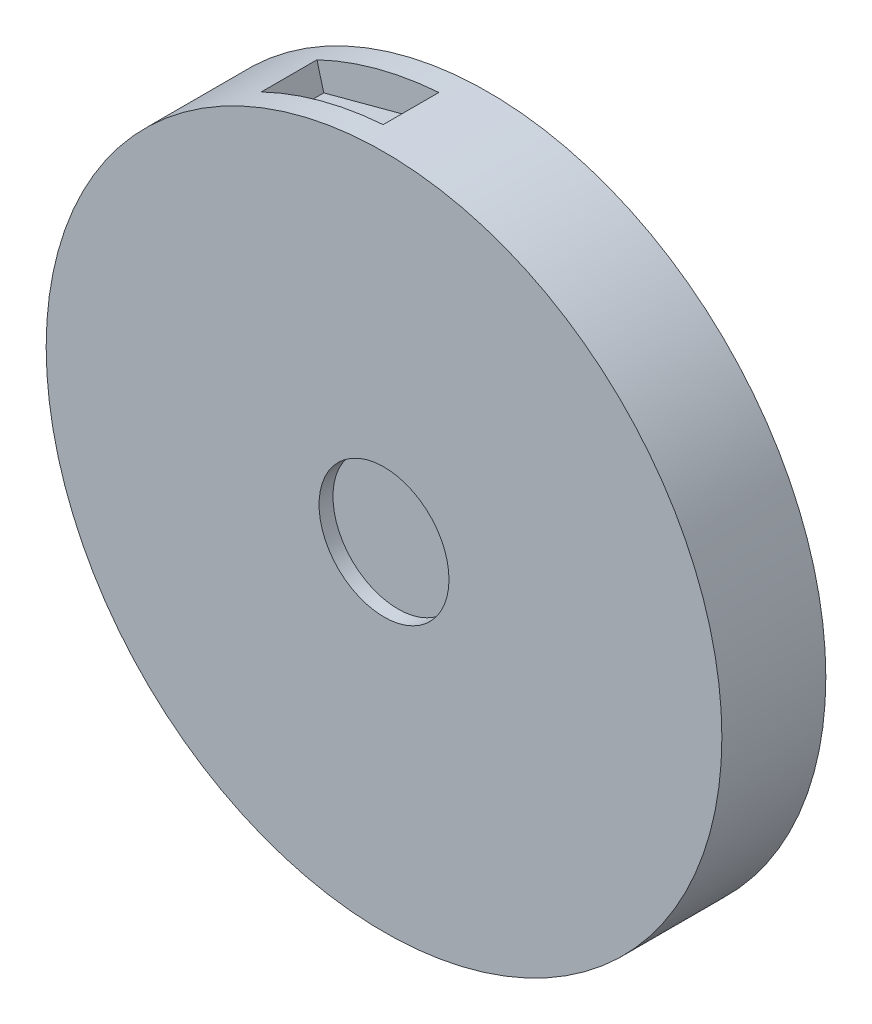
SolidWorks part; units mm, degrees
material "7075-T6, Plate (SS)"
ref_plane "Front" through (0, 0, 0) normal (0, 0, 1) x (1, 0, 0)
ref_plane "Top" through (0, 0, 0) normal (0, 1, 0) x (1, 0, 0)
ref_plane "Right" through (0, 0, 0) normal (1, 0, 0) x (0, 0, -1)
sketch "Sketch1" plane through (0, 0, 0) normal (0, 0, 1) x (1, 0, 0)
  circle A1 centre (0, 0) radius 18.2
  dimension "D1" = 36.4
extrude "Boss-Extrude1" add sketch "Sketch1" along normal blind 5.6 separate body
sketch "Sketch2" plane through (0, 0, 0) normal (0, 0, -1) x (-1, 0, 0)
  line L0 (-11.1314, -13.5034) -> (11.1314, 13.5034) construction
  line L1 (0, 0) -> (13.5086, 0) construction
  line L2 (0, 0) -> (15.6152, -12.8722) construction
  arc A2 (12.9625, -11.7568) -> (14.0142, -10.4811) centre (0, 0) ccw
  arc A3 (-12.4066, -12.1331) -> (-9.5429, -14.4937) centre (-11.4494, -13.8892) cw
  arc A4 (-9.5429, -14.4937) -> (-9.4604, -14.7225) centre (-9.3523, -14.5542) ccw
  arc A5 (-12.4066, -12.1331) -> (-12.6468, -12.0958) centre (-12.5023, -11.9575) cw
  arc A6 (12.4066, 12.1331) -> (12.6468, 12.0958) centre (12.5023, 11.9575) cw
  arc A7 (9.5429, 14.4937) -> (12.4066, 12.1331) centre (11.4494, 13.8892) ccw
  arc A8 (9.5429, 14.4937) -> (9.4604, 14.7225) centre (9.3523, 14.5542) ccw
  arc A10 (13.0025, -11.5546) -> (13.8233, -10.5589) centre (13.708, -11.3) cw
  arc A11 (13.8233, -10.5589) -> (14.0142, -10.4811) centre (13.854, -10.3613) ccw
  arc A12 (13.0025, -11.5546) -> (12.9625, -11.7568) centre (12.8144, -11.6224) cw
  arc A13 (12.6468, 12.0958) -> (9.4604, 14.7225) centre (0, 0) ccw
  arc A14 (-12.6468, -12.0958) -> (-9.4604, -14.7225) centre (0, 0) ccw
  dimension "D3" = 2
  dimension "D4" = 0.2
  dimension "D7" = 0.75
  dimension "D1" = 35
  dimension "D2" = 50.5
  dimension "D5" = 4.1295
  dimension "D6" = 1.6533
extrude "Cut-Extrude1" cut sketch "Sketch2" against normal blind 4
sketch "Sketch3" plane through (0, 0, 5.6) normal (0, 0, 1) x (1, 0, 0)
  circle A0 centre (0, 0) radius 3.5
  dimension "D1" = 7
extrude "Cut-Extrude2" cut sketch "Sketch3" against normal blind 0.75
sketch "Sketch4" plane through (0, 0, 0) normal (0, 1, 0) x (1, 0, 0)
  line L0 (0, 0) -> (0, 23.9004) construction
ref_plane "Plane1" through (0, 0, 0) normal (-0.2588, 0.9659, 0) x (0, 0, -1)
sketch "Sketch5" plane through (0, 0, 0) normal (-0.2588, 0.9659, 0) x (0, 0, -1)
  line L0 (0, 0) -> (23.9004, 0) construction
  line L1 (-4.3, 3.4) -> (-1.3, 3.4)
  line L2 (-4.3, 3.4) -> (-4.3, -3.4)
  line L3 (-4.3, -3.4) -> (-1.3, -3.4)
  line L4 (-1.3, 3.4) -> (-1.3, -3.4)
  line L5 (0, -18.2) -> (0, 18.2) construction
  point P4 (-1.3, 0)
  dimension "D1" = 3
  dimension "D2" = 6.8
  dimension "D3" = 1.3
extrude "Cut-Extrude3" cut sketch "Sketch5" along normal up to next from offset 16.47
